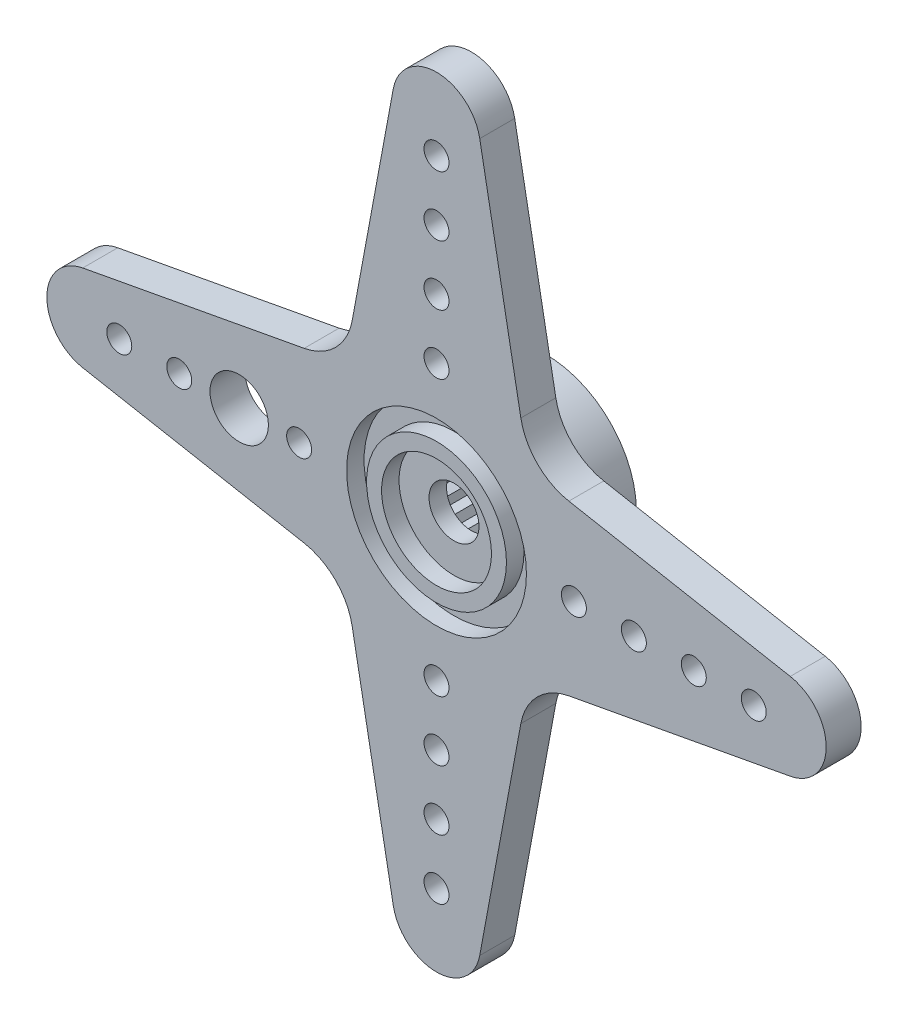
SolidWorks part; units mm, degrees
material "ABS"
ref_plane "Front Plane" through (0, 0, 0) normal (0, 0, 1) x (1, 0, 0)
ref_plane "Top Plane" through (0, 0, 0) normal (0, 1, 0) x (1, 0, 0)
ref_plane "Right Plane" through (0, 0, 0) normal (1, 0, 0) x (0, 0, -1)
sketch "Sketch1" plane through (0, 0, 0) normal (0, 0, 1) x (1, 0, 0)
  line L50 (-10.25, 3) -> (-10.5946, 2.7283)
  line L51 (-10.5946, 2.7283) -> (-10.996, 2.9057)
  line L52 (-10.996, 2.9057) -> (-11.2623, 2.5569)
  line L53 (-11.2623, 2.5569) -> (-11.6952, 2.6289)
  line L54 (-11.6952, 2.6289) -> (-11.8664, 2.2248)
  line L55 (-11.8664, 2.2248) -> (-12.3036, 2.1869)
  line L56 (-12.3036, 2.1869) -> (-12.3689, 1.7529)
  line L57 (-12.3689, 1.7529) -> (-12.7829, 1.6075)
  line L58 (-12.7829, 1.6075) -> (-12.7382, 1.1709)
  line L59 (-12.7382, 1.1709) -> (-13.1031, 0.927)
  line L60 (-13.1031, 0.927) -> (-12.9512, 0.5153)
  line L61 (-12.9512, 0.5153) -> (-13.244, 0.1884)
  line L62 (-13.244, 0.1884) -> (-12.9945, -0.1727)
  line L63 (-12.9945, -0.1727) -> (-13.1968, -0.5621)
  line L64 (-13.1968, -0.5621) -> (-12.8654, -0.8498)
  line L65 (-12.8654, -0.8498) -> (-12.9644, -1.2773)
  line L66 (-12.9644, -1.2773) -> (-12.5719, -1.4735)
  line L67 (-12.5719, -1.4735) -> (-12.5615, -1.9123)
  line L68 (-12.5615, -1.9123) -> (-12.1325, -2.0047)
  line L69 (-12.1325, -2.0047) -> (-12.0133, -2.427)
  line L70 (-12.0133, -2.427) -> (-11.5748, -2.4098)
  line L71 (-11.5748, -2.4098) -> (-11.3543, -2.7893)
  line L72 (-11.3543, -2.7893) -> (-10.9339, -2.6636)
  line L73 (-10.9339, -2.6636) -> (-10.626, -2.9763)
  line L74 (-10.626, -2.9763) -> (-10.25, -2.75)
  line L75 (-10.25, -2.75) -> (-9.874, -2.9763)
  line L76 (-9.874, -2.9763) -> (-9.5661, -2.6636)
  line L77 (-9.5661, -2.6636) -> (-9.1456, -2.7893)
  line L78 (-9.1456, -2.7893) -> (-8.9251, -2.4098)
  line L79 (-8.9251, -2.4098) -> (-8.4866, -2.427)
  line L80 (-8.4866, -2.427) -> (-8.3675, -2.0047)
  line L81 (-8.3675, -2.0047) -> (-7.9384, -1.9123)
  line L82 (-7.9384, -1.9123) -> (-7.9281, -1.4735)
  line L83 (-7.9281, -1.4735) -> (-7.5355, -1.2773)
  line L84 (-7.5355, -1.2773) -> (-7.6346, -0.8498)
  line L85 (-7.6346, -0.8498) -> (-7.3031, -0.5621)
  line L86 (-7.3031, -0.5621) -> (-7.5054, -0.1727)
  line L87 (-7.5054, -0.1727) -> (-7.2559, 0.1884)
  line L88 (-7.2559, 0.1884) -> (-7.5487, 0.5153)
  line L89 (-7.5487, 0.5153) -> (-7.3968, 0.927)
  line L90 (-7.3968, 0.927) -> (-7.7617, 1.1709)
  line L91 (-7.7617, 1.1709) -> (-7.717, 1.6075)
  line L92 (-7.717, 1.6075) -> (-8.1311, 1.7529)
  line L93 (-8.1311, 1.7529) -> (-8.1963, 2.1869)
  line L94 (-8.1963, 2.1869) -> (-8.6336, 2.2248)
  line L95 (-8.6336, 2.2248) -> (-8.8047, 2.6289)
  line L96 (-8.8047, 2.6289) -> (-9.2376, 2.5569)
  line L97 (-9.2376, 2.5569) -> (-9.5039, 2.9057)
  line L98 (-9.5039, 2.9057) -> (-9.9053, 2.7283)
  line L99 (-9.9053, 2.7283) -> (-10.25, 3)
  line L100 (-10.25, 3) -> (-10.5946, 2.7283)
  line L101 (-10.5946, 2.7283) -> (-10.996, 2.9057)
  line L102 (-10.996, 2.9057) -> (-11.2623, 2.5569)
  line L103 (-11.2623, 2.5569) -> (-11.6952, 2.6289)
  line L104 (-11.6952, 2.6289) -> (-11.8664, 2.2248)
  line L105 (-11.8664, 2.2248) -> (-12.3036, 2.1869)
  line L106 (-12.3036, 2.1869) -> (-12.3689, 1.7529)
  line L107 (-12.3689, 1.7529) -> (-12.7829, 1.6075)
  line L108 (-12.7829, 1.6075) -> (-12.7382, 1.1709)
  line L109 (-12.7382, 1.1709) -> (-13.1031, 0.927)
  line L110 (-13.1031, 0.927) -> (-12.9512, 0.5153)
  line L111 (-12.9512, 0.5153) -> (-13.244, 0.1884)
  line L112 (-13.244, 0.1884) -> (-12.9945, -0.1727)
  line L113 (-12.9945, -0.1727) -> (-13.1968, -0.5621)
  line L114 (-13.1968, -0.5621) -> (-12.8654, -0.8498)
  line L115 (-12.8654, -0.8498) -> (-12.9644, -1.2773)
  line L116 (-12.9644, -1.2773) -> (-12.5719, -1.4735)
  line L117 (-12.5719, -1.4735) -> (-12.5615, -1.9123)
  line L118 (-12.5615, -1.9123) -> (-12.1325, -2.0047)
  line L119 (-12.1325, -2.0047) -> (-12.0133, -2.427)
  line L120 (-12.0133, -2.427) -> (-11.5748, -2.4098)
  line L121 (-11.5748, -2.4098) -> (-11.3543, -2.7893)
  line L122 (-11.3543, -2.7893) -> (-10.9339, -2.6636)
  line L123 (-10.9339, -2.6636) -> (-10.626, -2.9763)
  line L124 (-10.626, -2.9763) -> (-10.25, -2.75)
  line L125 (-10.25, -2.75) -> (-9.874, -2.9763)
  line L126 (-9.874, -2.9763) -> (-9.5661, -2.6636)
  line L127 (-9.5661, -2.6636) -> (-9.1456, -2.7893)
  line L128 (-9.1456, -2.7893) -> (-8.9251, -2.4098)
  line L129 (-8.9251, -2.4098) -> (-8.4866, -2.427)
  line L130 (-8.4866, -2.427) -> (-8.3675, -2.0047)
  line L131 (-8.3675, -2.0047) -> (-7.9384, -1.9123)
  line L132 (-7.9384, -1.9123) -> (-7.9281, -1.4735)
  line L133 (-7.9281, -1.4735) -> (-7.5355, -1.2773)
  line L134 (-7.5355, -1.2773) -> (-7.6346, -0.8498)
  line L135 (-7.6346, -0.8498) -> (-7.3031, -0.5621)
  line L136 (-7.3031, -0.5621) -> (-7.5054, -0.1727)
  line L137 (-7.5054, -0.1727) -> (-7.2559, 0.1884)
  line L138 (-7.2559, 0.1884) -> (-7.5487, 0.5153)
  line L139 (-7.5487, 0.5153) -> (-7.3968, 0.927)
  line L140 (-7.3968, 0.927) -> (-7.7617, 1.1709)
  line L141 (-7.7617, 1.1709) -> (-7.717, 1.6075)
  line L142 (-7.717, 1.6075) -> (-8.1311, 1.7529)
  line L143 (-8.1311, 1.7529) -> (-8.1963, 2.1869)
  line L144 (-8.1963, 2.1869) -> (-8.6336, 2.2248)
  line L145 (-8.6336, 2.2248) -> (-8.8047, 2.6289)
  line L146 (-8.8047, 2.6289) -> (-9.2376, 2.5569)
  line L147 (-9.2376, 2.5569) -> (-9.5039, 2.9057)
  line L148 (-9.5039, 2.9057) -> (-9.9053, 2.7283)
  line L149 (-9.9053, 2.7283) -> (-10.25, 3)
  circle A0 centre (-10.25, 0) radius 4.5
  dimension "D2" = 9
  dimension "D1" = 0
extrude "Boss-Extrude1" add sketch "Sketch1" against normal blind 3.75 contours A0 L149 L148 L147 L146 L145 L144 L143 L142 L141 L140 L139 L138 L137 L136 L135 L134 L133 L132 L131 L130 L129 L128 L127 L126 L125 L124 L123 L122 L121 L120 L119 L118 L117 L116 L115 L114 L113 L112 L111 L110 L109 L108 L107 L106 L105 L104 L103 L102 L101
sketch "Sketch2" plane through (0, 0, 0) normal (0, 0, 1) x (1, 0, 0)
  circle A0 centre (-10.25, 0) radius 1.25
  circle A1 centre (-10.25, 0) radius 3.5
  circle A2 centre (-10.25, 0) radius 4.5
  dimension "D1" = 7
  dimension "D2" = 2.5
  dimension "D3" = 9
extrude "Boss-Extrude2" add sketch "Sketch2" along normal blind 1.75 contours A2 A1 | A1 A0
sketch "Sketch4" plane through (0, 0, 1.75) normal (0, 0, 1) x (1, 0, 0)
  circle A0 centre (-10.25, 0) radius 3.5
  circle A1 centre (-10.25, 0) radius 2.75
  circle M2 centre (-10.25, 0) radius 1.25
  dimension "D1" = 7
  dimension "D2" = 0.75
extrude "Cut-Extrude1" cut sketch "Sketch4" against normal blind 0.875 contours A1 M2
sketch "Sketch6" plane through (0, 0, 1.75) normal (0, 0, 1) x (1, 0, 0)
  circle A0 centre (-10.25, 0) radius 3.5
  circle A1 centre (-10.25, 0) radius 2.75 construction
  circle A2 centre (-10.25, 0) radius 4.5
  circle M2 centre (-10.25, 0) radius 4.5
  dimension "D1" = 0.75
  dimension "D2" = 9
extrude "Cut-Extrude2" cut sketch "Sketch6" against normal blind 0.875 contours A0 M2
sketch "Sketch7" [suppressed] plane through (0, 0, 1.75) normal (0, 0, 1) x (1, 0, 0)
  circle A0 centre (-10.25, 0) radius 10.5
  circle A1 centre (-10.25, 0) radius 4.5
  dimension "D1" = 21
extrude "Boss-Extrude3" [suppressed] add sketch "Sketch7" against normal blind 1.75
sketch "Sketch9" [suppressed] plane through (0, 0, 1.75) normal (0, 0, 1) x (1, 0, 0)
  line L0 (-10.25, 0) -> (-10.25, 11.6833) construction
  circle A0 centre (-10.25, 7.875) radius 0.625
  circle A1 centre (-14.125, 7.875) radius 0.625
  circle A2 centre (-10.25, 0) radius 10.5 construction
  circle A3 centre (-6.375, 7.875) radius 0.625
  dimension "D1" = 2
  dimension "D2" = 1.25
  dimension "D3" = 1.25
  dimension "D4" = 2.625
extrude "Cut-Extrude3" [suppressed] cut sketch "Sketch9" against normal through all
pattern_circular "CirPattern1" [suppressed] count 4 over 360
chamfer "Chamfer1" [suppressed] distance 1 angle 30
sketch "Sketch10" plane through (0, 0, 1.75) normal (0, 0, 1) x (1, 0, 0)
  line L0 (-10.25, 0) -> (-10.25, 9.0053) construction
  line L1 (-10.25, 0) -> (0.0732, 10.3232) construction
  line L2 (-10.25, 0) -> (1.1009, 0) construction
  line L3 (-8.0869, 17.7016) -> (-6.0299, 6.622)
  line L4 (-3.6279, 4.2201) -> (7.4516, 2.163)
  line L5 (7.4516, -2.163) -> (-3.6279, -4.2201)
  line L6 (-6.0299, -6.622) -> (-8.0869, -17.7016)
  line L7 (-12.413, -17.7016) -> (-14.47, -6.622)
  line L8 (-16.872, -4.2201) -> (-27.9515, -2.163)
  line L9 (-27.9515, 2.163) -> (-16.872, 4.2201)
  line L10 (-14.47, 6.622) -> (-12.413, 17.7016)
  arc A0 (-8.0869, 17.7016) -> (-10.25, 19.5) centre (-10.25, 17.3) ccw
  arc A1 (7.4516, -2.163) -> (7.4516, 2.163) centre (7.05, 0) ccw
  arc A2 (-6.0299, 6.622) -> (-3.6279, 4.2201) centre (-3.0803, 7.1697) ccw
  circle A3 centre (-10.25, 15.875) radius 0.625
  circle A4 centre (-10.25, 12.875) radius 0.625
  circle A5 centre (-10.25, 9.875) radius 0.625
  circle A6 centre (-10.25, 6.875) radius 0.625
  arc A7 (7.4516, -2.163) -> (9.25, 0) centre (7.05, 0) ccw
  circle A8 centre (5.625, 0) radius 0.625
  circle A9 centre (2.625, 0) radius 0.625
  circle A10 centre (-0.375, 0) radius 0.625
  circle A11 centre (-3.375, 0) radius 0.625
  arc A12 (-3.6279, -4.2201) -> (-6.0299, -6.622) centre (-3.0803, -7.1697) ccw
  arc A13 (-12.413, -17.7016) -> (-8.0869, -17.7016) centre (-10.25, -17.3) ccw
  arc A14 (-12.413, -17.7016) -> (-10.25, -19.5) centre (-10.25, -17.3) ccw
  circle A15 centre (-10.25, -15.875) radius 0.625
  circle A16 centre (-10.25, -12.875) radius 0.625
  circle A17 centre (-10.25, -9.875) radius 0.625
  circle A18 centre (-10.25, -6.875) radius 0.625
  arc A19 (-14.47, -6.622) -> (-16.872, -4.2201) centre (-17.4196, -7.1697) ccw
  arc A20 (-27.9515, 2.163) -> (-27.9515, -2.163) centre (-27.5499, 0) ccw
  arc A21 (-27.9515, 2.163) -> (-29.7499, 0) centre (-27.5499, 0) ccw
  circle A22 centre (-26.1249, 0) radius 0.625
  circle A23 centre (-23.1249, 0) radius 0.625
  circle A24 centre (-20.1249, 0) radius 0.625
  circle A25 centre (-17.1249, 0) radius 0.625
  arc A26 (-16.872, 4.2201) -> (-14.47, 6.622) centre (-17.4196, 7.1697) ccw
  arc A27 (-8.0869, 17.7016) -> (-12.413, 17.7016) centre (-10.25, 17.3) ccw
  circle A28 centre (-10.25, 0) radius 4.5
  point P1 (-10.25, 0)
  point P10 (-5.6538, 4.5962)
  point P20 (-5.6538, 4.5962)
  point P21 (-10.25, 19.5)
  point P84 (-10.25, 0)
  circle M4 centre (-10.25, 0) radius 3.5
  dimension "D2" = 19.5
  dimension "D3" = 19.5
  dimension "D4" = 4.4
  dimension "D5" = 4.4
  dimension "D7" = 3
  dimension "D8" = 1.25
  dimension "D9" = 3
  dimension "D1" = 45
  dimension "D6" = 6.5
  dimension "D10" = 4
  dimension "D11" = 4
extrude "Boss-Extrude4" add sketch "Sketch10" against normal blind 1.75 contours A0 A27 L10 A26 L9 A20 L8 A19 L7 A13 L6 A12 L5 A1 L4 A2 L3 A3 A4 A5 A6 A8 A9 A10 A11 A15 A16 A17 A18 A22 A23 M4
chamfer "Chamfer2" distance 1 angle 30 1 edges at (-5.75, 0, 0)
sketch "Sketch11" [suppressed] plane through (0, 0, 1.75) normal (0, 0, 1) x (1, 0, 0)
  line L0 (-10.25, 0) -> (-10.25, 17.5605) construction
  line L1 (-10.25, 0) -> (4.9579, 8.7803) construction
  line L2 (-10.25, 0) -> (4.9579, -8.7803) construction
  line L3 (-10.25, 0) -> (-10.25, -17.5605) construction
  line L4 (-10.25, 0) -> (-25.4578, -8.7803) construction
  line L5 (-10.25, 0) -> (-25.4578, 8.7803) construction
  line L6 (-10.25, 0) -> (-3.969, 10.8789) construction
  line L7 (-10.25, 0) -> (2.312, 0) construction
  line L8 (-10.25, 0) -> (-3.969, -10.8789) construction
  line L9 (-10.25, 0) -> (-16.5309, -10.8789) construction
  line L10 (-10.25, 0) -> (-22.8119, 0) construction
  line L11 (-10.25, 0) -> (-16.5309, 10.8789) construction
  line L12 (-8.5769, 14.5133) -> (-6.25, 6.9282)
  line L13 (-6.25, 6.9282) -> (1.4824, 8.7055)
  line L14 (3.1554, 5.8077) -> (-2.25, 0)
  line L15 (-2.25, 0) -> (3.1554, -5.8077)
  line L16 (1.4824, -8.7055) -> (-6.25, -6.9282)
  line L17 (-6.25, -6.9282) -> (-8.5769, -14.5133)
  line L18 (-11.923, -14.5133) -> (-14.25, -6.9282)
  line L19 (-14.25, -6.9282) -> (-21.9823, -8.7055)
  line L20 (-23.6553, -5.8077) -> (-18.25, 0)
  line L21 (-18.25, 0) -> (-23.6553, 5.8077)
  line L22 (-21.9823, 8.7055) -> (-14.25, 6.9282)
  line L23 (-14.25, 6.9282) -> (-11.923, 14.5133)
  circle A0 centre (-10.25, 0) radius 4.5
  arc A1 (-8.5769, 14.5133) -> (-10.25, 15.75) centre (-10.25, 14) ccw
  arc A2 (3.3899, 7.875) -> (1.4824, 8.7055) centre (1.8744, 7) ccw
  circle A4 centre (-10.25, 13.375) radius 0.625
  circle A5 centre (-10.25, 10.375) radius 0.625
  circle A6 centre (-10.25, 7.375) radius 0.625
  circle A7 centre (1.3331, 6.6875) radius 0.625
  arc A8 (3.1554, 5.8077) -> (3.3899, 7.875) centre (1.8744, 7) ccw
  circle A9 centre (-1.2649, 5.1875) radius 0.625
  circle A10 centre (-3.863, 3.6875) radius 0.625
  arc A11 (3.3899, -7.875) -> (3.1554, -5.8077) centre (1.8744, -7) ccw
  circle A12 centre (1.3331, -6.6875) radius 0.625
  arc A13 (1.4824, -8.7055) -> (3.3899, -7.875) centre (1.8744, -7) ccw
  circle A14 centre (-1.2649, -5.1875) radius 0.625
  circle A15 centre (-3.863, -3.6875) radius 0.625
  arc A16 (-10.25, -15.75) -> (-8.5769, -14.5133) centre (-10.25, -14) ccw
  circle A17 centre (-10.25, -13.375) radius 0.625
  arc A18 (-11.923, -14.5133) -> (-10.25, -15.75) centre (-10.25, -14) ccw
  circle A19 centre (-10.25, -10.375) radius 0.625
  circle A20 centre (-10.25, -7.375) radius 0.625
  arc A21 (-23.8899, -7.875) -> (-21.9823, -8.7055) centre (-22.3743, -7) ccw
  circle A22 centre (-21.833, -6.6875) radius 0.625
  arc A23 (-23.6553, -5.8077) -> (-23.8899, -7.875) centre (-22.3743, -7) ccw
  circle A24 centre (-19.235, -5.1875) radius 0.625
  circle A25 centre (-16.6369, -3.6875) radius 0.625
  arc A26 (-23.8899, 7.875) -> (-23.6553, 5.8077) centre (-22.3743, 7) ccw
  circle A27 centre (-21.833, 6.6875) radius 0.625
  arc A28 (-21.9823, 8.7055) -> (-23.8899, 7.875) centre (-22.3743, 7) ccw
  circle A29 centre (-19.235, 5.1875) radius 0.625
  circle A30 centre (-16.6369, 3.6875) radius 0.625
  arc A31 (-10.25, 15.75) -> (-11.923, 14.5133) centre (-10.25, 14) ccw
  point P5 (-10.25, 0)
  point P12 (-10.25, 0)
  point P20 (-10.25, 0)
  point P22 (-6.25, 6.9282)
  point P26 (-10.25, 15.75)
  point P27 (3.3899, 7.875)
  point P102 (-10.25, 0)
  dimension "D4" = 15.75
  dimension "D5" = 15.75
  dimension "D6" = 3.5
  dimension "D7" = 3.5
  dimension "D9" = 1.25
  dimension "D10" = 1.75
  dimension "D2" = 30
  dimension "D8" = 8
  dimension "D11" = 3
  dimension "D1" = 6
  dimension "D3" = 6
  dimension "D12" = 6
extrude "Boss-Extrude5" [suppressed] add sketch "Sketch11" against normal blind 1.75 contours A1 A31 L23 L22 A28 A26 L21 L20 A23 A21 L19 L18 A18 A16 L17 L16 A13 A11 L15 L14 A8 A2 L13 L12 A0 A4 A5 A6 A7 A9 A10 A12 A14 A15 A17 A19 A20
chamfer "Chamfer4" [suppressed] distance 1 angle 30
sketch "Sketch12" [suppressed] plane through (0, 0, 0.875) normal (0, 0, 1) x (1, 0, 0)
  circle A0 centre (-10.25, 0) radius 1.25
  circle A1 centre (-10.25, 0) radius 5
extrude "Boss-Extrude6" [suppressed] add sketch "Sketch12" along normal blind 0.125
sketch "Sketch14" [suppressed] plane through (0, 0, 1) normal (0, 0, 1) x (1, 0, 0)
  line L0 (-10.25, 0) -> (-28.2499, 0) construction
  line L1 (-10.25, -6) -> (-28.2499, -6)
  line L2 (-10.25, 6) -> (-28.2499, 6)
  arc A0 (-10.25, -6) -> (-10.25, 6) centre (-10.25, 0) ccw
  arc A1 (-28.2499, 6) -> (-28.2499, -6) centre (-28.2499, 0) ccw
  point P4 (-19.2499, 0)
  dimension "D1" = 12
  dimension "D2" = 29.9999
extrude "Boss-Extrude7" [suppressed] add sketch "Sketch14" along normal blind 3
sketch "Sketch16" [suppressed] plane through (0, 0, 1) normal (0, 0, -1) x (-1, 0, 0)
  line L0 (25.9999, 0) -> (30.4999, 0) construction
  line L1 (25.9999, 2.75) -> (30.4999, 2.75)
  line L2 (25.9999, -2.75) -> (30.4999, -2.75)
  arc A0 (25.9999, 2.75) -> (25.9999, -2.75) centre (25.9999, 0) ccw
  arc A1 (30.4999, -2.75) -> (30.4999, 2.75) centre (30.4999, 0) ccw
  arc A10 (28.2499, -6) -> (28.2499, 6) centre (28.2499, 0) ccw construction
  point P3 (28.2499, 0)
  point P8 (34.2499, 0)
  point P9 (33.2499, 0)
  dimension "D2" = 10
  dimension "D3" = 1
  dimension "D1" = 5.5
extrude "Boss-Extrude8" [suppressed] add sketch "Sketch16" along normal blind 2.75 contours L1 A1 L2 A0
sketch "Sketch17" [suppressed] plane through (0, 0, -1.75) normal (0, 0, -1) x (-1, 0, 0)
  circle A0 centre (30.7499, 0) radius 1.5
  circle A1 centre (25.7499, 0) radius 1.5
  arc A5 (28.2499, -6) -> (28.2499, 6) centre (28.2499, 0) ccw construction
  dimension "D1" = 3
  dimension "D2" = 3
  dimension "D3" = 2
  dimension "D4" = 2
extrude "Cut-Extrude4" [suppressed] cut sketch "Sketch17" against normal through all
sketch "Sketch18" [suppressed] plane through (0, 0, 1) normal (0, 0, -1) x (-1, 0, 0)
  circle A0 centre (10.25, 0) radius 3
  dimension "D1" = 6
extrude "Cut-Extrude5" [suppressed] cut sketch "Sketch18" against normal through all
sketch "Sketch19" [suppressed] plane through (0, 0, 1.5) normal (0, 0, 1) x (1, 0, 0)
  line L0 (-35.7499, 0) -> (15.25, 0) construction
  line L1 (-9.625, 5.9674) -> (14.1146, 3.481)
  line L2 (14.1146, -3.481) -> (-9.625, -5.9674)
  line L3 (-10.25, 0) -> (-10.25, 10.691) construction
  line L4 (-34.6145, -3.481) -> (-10.875, -5.9674)
  line L5 (-10.875, 5.9674) -> (-34.6145, 3.481)
  circle A0 centre (-10.25, 0) radius 6
  arc A1 (14.1146, -3.481) -> (14.1146, 3.481) centre (13.75, 0) ccw
  circle A2 centre (14.625, 0) radius 0.625
  circle A3 centre (11.375, 0) radius 0.625
  circle A4 centre (8.125, 0) radius 0.625
  circle A5 centre (4.875, 0) radius 0.625
  circle A6 centre (1.625, 0) radius 0.625
  circle A7 centre (-22.1249, 0) radius 0.625
  circle A8 centre (-25.3749, 0) radius 0.625
  circle A9 centre (-28.6249, 0) radius 0.625
  circle A10 centre (-31.8749, 0) radius 0.625
  circle A11 centre (-35.1249, 0) radius 0.625
  arc A12 (-34.6145, -3.481) -> (-34.6145, 3.481) centre (-34.2499, 0) cw
  point P37 (-10.25, -6)
  circle M5 centre (-10.25, 0) radius 5
  circle M6 centre (-10.25, 0) radius 1.25
  dimension "D1" = 12
  dimension "D2" = 7
  dimension "D4" = 1.25
  dimension "D5" = 2
  dimension "D3" = 27.4999
  dimension "D6" = 5
extrude "Boss-Extrude9" [suppressed] add sketch "Sketch19" along normal blind 2.5 contours A12 L4 A0 L5 A10 A8 A7 A9 A11 | A0 M5 | M5 M6 | L2 A1 L1 A0 A6 A5 A4 A3 A2
sketch "Sketch20" [suppressed] plane through (0, 0, 4) normal (0, 0, 1) x (1, 0, 0)
  arc A0 (-9.625, 5.9674) -> (-10.875, 5.9674) centre (-10.25, 0) ccw construction
  circle A1 centre (-10.25, 0) radius 4
  circle A2 centre (-10.25, 0) radius 6
  point P5 (-10.25, 4)
  point P7 (-10.25, -4)
  dimension "D1" = 2
extrude "Boss-Extrude10" [suppressed] add sketch "Sketch20" along normal blind 1
sketch "Sketch21" [suppressed] plane through (0, 0, 4) normal (0, 0, 1) x (1, 0, 0)
  circle A0 centre (-10.25, 0) radius 4 construction
  circle A1 centre (-10.25, 0) radius 4
  circle A2 centre (-10.25, 0) radius 3.25
  dimension "D1" = 0.75
extrude "Boss-Extrude11" [suppressed] add sketch "Sketch21" along normal offset from surface (0.5 mm away) 0.5
sketch "Sketch22" [suppressed] plane through (0, 0, 4) normal (0, 0, 1) x (1, 0, 0)
  circle A0 centre (-10.25, 0) radius 3.25
extrude "Cut-Extrude6" [suppressed] cut sketch "Sketch22" against normal offset from surface (3 mm away) 1 contours A0
chamfer "Chamfer5" [suppressed] distance 0.75 angle 45
ref_plane "Plane1" [suppressed] through (0, 4.5, 0) normal (0, 1, 0) x (1, 0, 0)
ref_plane "Plane3" [suppressed] through (0, 0.5, 0) normal (0, 1, 0) x (1, 0, 0)
sketch "Sketch26" [suppressed] plane through (0, 0.5, 0) normal (0, 1, 0) x (1, 0, 0)
  line L0 (-17.4408, -4) -> (-16.1908, -5)
  line L1 (-10.875, -4) -> (-34.6145, -4) construction
  line L2 (-16.1908, -5) -> (-15.6228, -4)
  line L3 (-15.6228, -4) -> (-17.4408, -4)
  line L4 (-16.25, -5) -> (-4.25, -5) construction
  dimension "D1" = 1.25
extrude "Boss-Extrude15" [suppressed] add sketch "Sketch26" against normal blind 1
ref_plane "Plane4" [suppressed] through (0, 5, 0) normal (0, 1, 0) x (1, 0, 0)
sketch "Sketch27" [suppressed] plane through (0, 5, 0) normal (0, 1, 0) x (1, 0, 0)
  line L0 (-17.4408, -4) -> (-13.2508, -4)
  line L1 (-16.1908, -5) -> (-13.2508, -5)
  line L3 (-17.4408, -4) -> (-16.1908, -5)
  line L4 (-16.1908, -5) -> (-15.6228, -4)
  line L5 (-15.6228, -4) -> (-17.4408, -4)
  line L6 (-17.4408, -4) -> (-16.1908, -5)
  line L10 (-13.2508, -5) -> (-13.2508, -4)
  dimension "D1" = 0
extrude "Boss-Extrude16" [suppressed] add sketch "Sketch27" against normal blind 1 contours L6 L1 L10 L0
mirror "Mirror1" [suppressed] about plane through (0, 0, 0) normal (0, 1, 0)
ref_plane "Plane5" [suppressed] through (-10.25, 0, 0) normal (1, 0, 0) x (0, 0, -1)
mirror "Mirror2" [suppressed] about plane through (-10.25, 0, 0) normal (1, 0, 0)
ref_plane "Plane6" [suppressed] through (0, 0, 2.75) normal (0, 0, 1) x (1, 0, 0)
mirror "Mirror3" [suppressed] about plane through (0, 0, 2.75) normal (0, 0, 1)
mirror "Mirror4" [suppressed] about plane through (-10.25, 0, 0) normal (1, 0, 0)
sketch "Sketch29" [suppressed] plane through (0, -5, 0) normal (0, -1, 0) x (1, 0, 0)
  line L0 (-15.25, 1.5) -> (-5.25, 1.5) construction
  line L1 (-13.2508, 0.5) -> (-7.2491, 0.5)
  line L2 (-13.2508, 0.5) -> (-13.2508, 1.5)
  line L3 (-13.2508, 1.5) -> (-7.2491, 1.5)
  line L4 (-7.2491, 0.5) -> (-7.2491, 1.5)
  line L5 (-7.2491, 0.5) -> (-7.2491, 1.5) construction
extrude "Boss-Extrude17" [suppressed] add sketch "Sketch29" against normal up to surface (1 mm away)
sketch "Sketch31" [suppressed] plane through (0, 0, 5) normal (0, 0, 1) x (1, 0, 0)
  line L1 (-19.5679, -7.6233) -> (-0.9321, -7.6233)
  line L2 (-19.5679, -7.6233) -> (-19.5679, 7.6233)
  line L3 (-19.5679, 7.6233) -> (-0.9321, 7.6233)
  line L4 (-0.9321, -7.6233) -> (-0.9321, 7.6233)
  line L5 (-19.5679, -7.6233) -> (-0.9321, 7.6233) construction
  line L6 (-19.5679, 7.6233) -> (-0.9321, -7.6233) construction
  point P0 (-10.25, 0)
  point P1 (-10.25, 0)
extrude "Cut-Extrude7" [suppressed] cut sketch "Sketch31" against normal blind 0.7493
ref_plane "Plane7" through (-10.25, 0, 0) normal (1, 0, 0) x (0, 0, -1)
sketch "Sketch32" plane through (0, 0, 0) normal (0, 0, -1) x (-1, 0, 0)
  circle A0 centre (20.1249, 0) radius 1.4605
  point P15 (10.25, 0)
  dimension "D1" = 2.921
extrude "Cut-Extrude8" cut sketch "Sketch32" against normal through all
